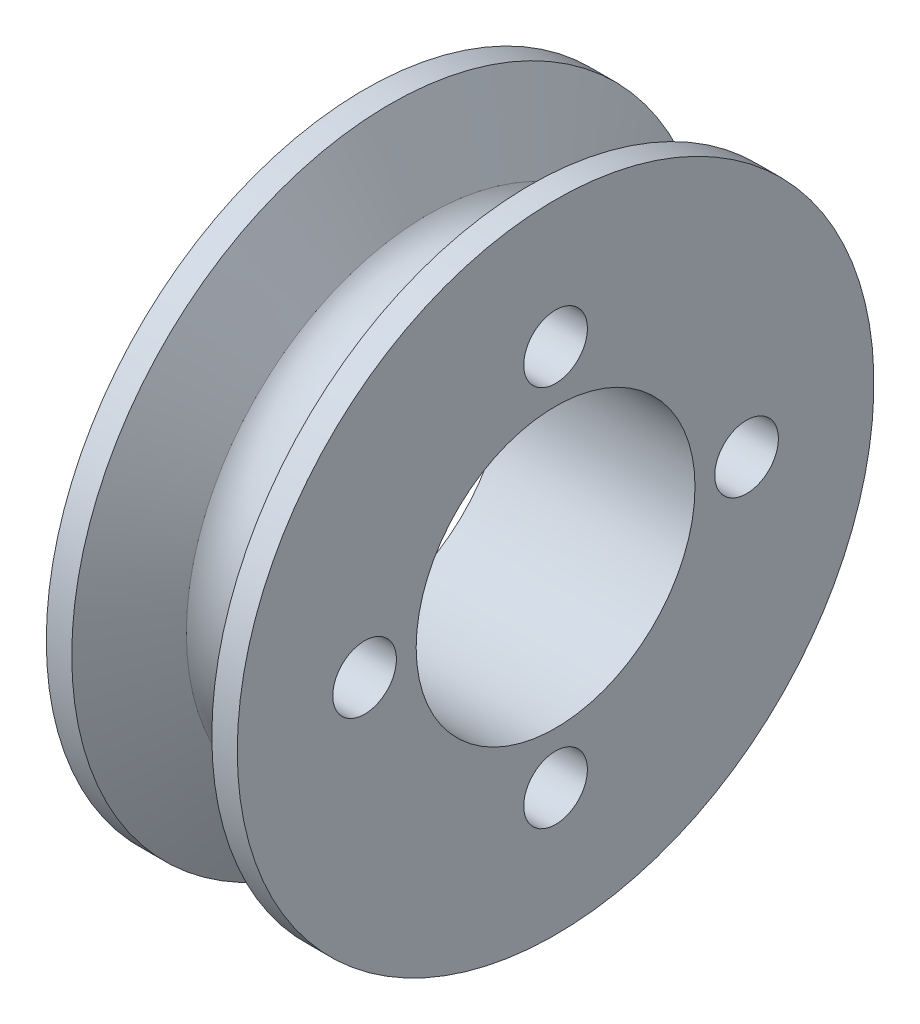
SolidWorks part; units mm, degrees
ref_plane "Alzado" through (0, 0, 0) normal (0, 0, 1) x (1, 0, 0)
ref_plane "Planta" through (0, 0, 0) normal (0, 1, 0) x (1, 0, 0)
ref_plane "Vista lateral" through (0, 0, 0) normal (1, 0, 0) x (0, 0, -1)
sketch "Croquis1" plane through (0, 0, 0) normal (0, 0, 1) x (1, 0, 0)
  line L0 (5.9522, 4.7456) -> (7.9522, 4.7456)
  line L1 (-7.0478, 4.7456) -> (-5.0478, 4.7456)
  line L2 (-7.0478, 4.7456) -> (-7.0478, -20.2544)
  line L3 (-7.0478, -20.2544) -> (7.9522, -20.2544)
  line L4 (7.9522, 4.7456) -> (7.9522, -20.2544)
  line L5 (-20.8444, -20.2544) -> (16.9874, -20.2544) construction
  line L7 (-7.0478, 4.7456) -> (-5.0478, 4.7456)
  line L8 (7.9522, 4.7456) -> (5.9522, 4.7456)
  line L9 (-5.0478, 4.7456) -> (-2.0478, -1.2544)
  line L11 (5.9522, 4.7456) -> (2.9522, -1.2544)
  arc A0 (2.9522, -1.2544) -> (-2.0478, -1.2544) centre (0.4522, 0.7456) cw
  point P0 (0, 0)
  dimension "D5" = 4
  dimension "D1" = 15
  dimension "D2" = 25
  dimension "D3" = 2
  dimension "D4" = 2
revolve "Revolución1" add sketch "Croquis1" angle 360 about L5
sketch "Croquis2" plane through (-7.0478, 0, 0) normal (-1, 0, 0) x (0, 0, 1)
  circle A0 centre (0, -20.2544) radius 3.95
  dimension "D1" = 7.9
extrude "Cortar-Extruir1" cut sketch "Croquis2" against normal blind 14
sketch "Croquis3" plane through (-7.0478, 0, 0) normal (-1, 0, 0) x (0, 0, 1)
  circle A0 centre (0, -20.2544) radius 10.95
  dimension "D1" = 21.9
extrude "Cortar-Extruir2" cut sketch "Croquis3" against normal blind 115.8
ref_plane "Plano1" through (7.9522, 0, 0) normal (1, 0, 0) x (0, 0, -1)
sketch "Croquis4" plane through (7.9522, 0, 0) normal (1, 0, 0) x (0, 0, -1)
  circle A2 centre (-15, -20.2544) radius 2.5
  circle A3 centre (0, -35.2544) radius 2.5
  circle A4 centre (15, -20.2544) radius 2.5
  circle A5 centre (0, -5.2544) radius 2.5
  dimension "D6" = 5
  dimension "D7" = 5
  dimension "D8" = 5
  dimension "D9" = 5
extrude "Cortar-Extruir3" cut sketch "Croquis4" against normal blind 43
